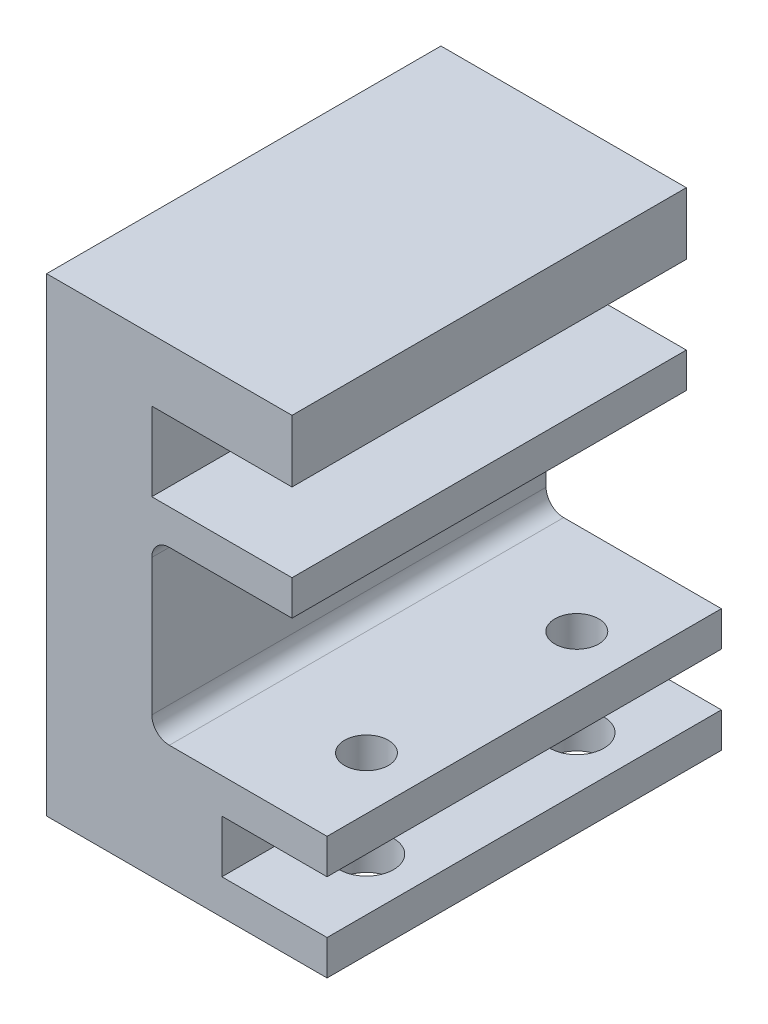
SolidWorks part; units mm, degrees
ref_plane "Front Plane" through (0, 0, 0) normal (0, 0, 1) x (1, 0, 0)
ref_plane "Top Plane" through (0, 0, 0) normal (0, 1, 0) x (1, 0, 0)
ref_plane "Right Plane" through (0, 0, 0) normal (1, 0, 0) x (0, 0, -1)
sketch "Sketch1" plane through (0, 0, 0) normal (0, 0, 1) x (1, 0, 0)
  line L1 (-25.4, -42.545) -> (25.4, -42.545)
  line L2 (-25.4, -42.545) -> (-25.4, 42.545)
  line L3 (-25.4, 42.545) -> (25.4, 42.545)
  line L4 (25.4, -42.545) -> (25.4, 42.545)
  line L5 (-25.4, -42.545) -> (25.4, 42.545) construction
  line L6 (-25.4, 42.545) -> (25.4, -42.545) construction
  point P0 (0, 0)
  dimension "D1" = 85.09
  dimension "D2" = 50.8
extrude "Boss-Extrude1" add sketch "Sketch1" along normal mid plane 71.4248
sketch "Sketch2" plane through (0, 0, 35.7124) normal (0, 0, 1) x (1, 0, 0)
  line L0 (-25.4, -42.545) -> (25.4, -42.545) construction
  line L1 (-6.35, 10.7252) -> (25.4, 10.7252)
  line L2 (-6.35, 10.7252) -> (-6.35, -20.32)
  line L3 (-6.35, -20.32) -> (25.4, -20.32)
  line L4 (25.4, 10.7252) -> (25.4, -20.32)
  line L5 (-6.35, 10.7252) -> (25.4, -20.32) construction
  line L6 (-6.35, -20.32) -> (25.4, 10.7252) construction
  line L7 (25.4, -42.545) -> (25.4, 42.545) construction
  point P0 (9.525, -4.7974)
  point P9 (-3.745, 20.5671)
  dimension "D1" = 22.225
  dimension "D2" = 31.0451
  dimension "D3" = 31.75
extrude "Cut-Extrude1" cut sketch "Sketch2" against normal up to next
ref_plane "Plane1" through (3.9688, 28.8925, -16.6687) normal (1, 0, 0) x (0, 0, -1)
sketch "Sketch4" plane through (0, 0, 35.7124) normal (0, 0, 1) x (1, 0, 0)
  line L0 (25.4, 10.7252) -> (25.4, 42.545) construction
  line L1 (-6.35, 17.0752) -> (25.4, 17.0752)
  line L2 (-6.35, 17.0752) -> (-6.35, 31.2992)
  line L3 (-6.35, 31.2992) -> (25.4, 31.2992)
  line L4 (25.4, 17.0752) -> (25.4, 31.2992)
  line L5 (-6.35, 17.0752) -> (25.4, 31.2992) construction
  line L6 (-6.35, 31.2992) -> (25.4, 17.0752) construction
  line L7 (-6.35, 10.7252) -> (-6.35, -20.32) construction
  line L8 (25.4, 10.7252) -> (-6.35, 10.7252) construction
  point P0 (9.525, 24.1872)
  dimension "D1" = 6.35
  dimension "D2" = 14.224
extrude "Cut-Extrude2" cut sketch "Sketch4" against normal through all
sketch "Sketch5" plane through (0, 0, 35.7124) normal (0, 0, 1) x (1, 0, 0)
  line L1 (6.35, -36.195) -> (25.4, -36.195)
  line L2 (6.35, -36.195) -> (6.35, -26.67)
  line L3 (6.35, -26.67) -> (25.4, -26.67)
  line L4 (25.4, -36.195) -> (25.4, -26.67)
  line L5 (6.35, -36.195) -> (25.4, -26.67) construction
  line L6 (6.35, -26.67) -> (25.4, -36.195) construction
  point P0 (15.875, -31.4325)
  point P5 (0, 0)
  point P7 (0, 0)
extrude "Cut-Extrude3" cut sketch "Sketch5" against normal up to next
sketch "Sketch6" plane through (0, 0, 35.7124) normal (0, 0, 1) x (1, 0, 0)
  line L0 (25.4, 10.7252) -> (-6.35, 10.7252) construction
  line L1 (19.05, 42.545) -> (25.4, 42.545)
  line L2 (19.05, 42.545) -> (19.05, 10.7252)
  line L3 (19.05, 10.7252) -> (25.4, 10.7252)
  line L4 (25.4, 42.545) -> (25.4, 10.7252)
  line L5 (19.05, 42.545) -> (25.4, 10.7252) construction
  line L6 (19.05, 10.7252) -> (25.4, 42.545) construction
  point P0 (22.225, 26.6351)
  point P5 (26.6487, -0.3804)
  point P6 (0, 0)
  point P8 (20.1934, 4.9427)
  dimension "D1" = 6.35
extrude "Cut-Extrude4" cut sketch "Sketch6" against normal up to next and the other way through all
sketch "Sketch7" plane through (-25.4, 0, 0) normal (-1, 0, 0) x (0, 0, 1)
  circle A0 centre (0, 24.13) radius 1.65 construction
  point P0 (0, 24.13)
hole_wizard "#10 Clearance Hole1" positions "Sketch8" profile "Sketch9" hole size "#10" standard "ANSI Inch" end condition up to next
sketch "Sketch8" plane through (-25.4, 0, 0) normal (-1, 0, 0) x (0, 0, 1)
  point P0 (0, 24.13)
sketch "Sketch9" plane through (-25.4, 24.13, 0) normal (0, 1, 0) x (0, 0, 1)
  line L0 (0, 0) -> (0, 19.05)
  line L1 (0, 19.05) -> (2.4892, 19.05)
  line L2 (2.4892, 19.05) -> (2.4892, 0)
  line L5 (2.4892, 0) -> (0, 0)
  line L11 (0, -6.35) -> (0, 107.95) construction
  dimension "Thru Hole Dia." = 4.9784
  dimension "Thru Hole Depth" = 19.05
sketch "Sketch10" plane through (0, -42.545, 0) normal (0, -1, 0) x (1, 0, 0)
  point P0 (15.875, 19.05)
  point P1 (15.875, -19.05)
hole_wizard "3/8 Clearance Hole1" positions "Sketch11" profile "Sketch12" hole size "3/8" standard "ANSI Inch"
sketch "Sketch11" plane through (0, -42.545, 0) normal (0, -1, 0) x (-1, 0, 0)
  point P0 (-15.875, -19.05)
  point P3 (-15.875, 19.05)
sketch "Sketch12" plane through (15.875, -42.545, 19.05) normal (1, 0, 0) x (0, 0, -1)
  line L0 (0, 0) -> (0, 6.35)
  line L1 (0, 6.35) -> (4.9022, 6.35)
  line L2 (4.9022, 6.35) -> (4.9022, 0)
  line L5 (4.9022, 0) -> (0, 0)
  line L11 (0, -6.35) -> (0, 107.95) construction
  dimension "Thru Hole Dia." = 9.8044
  dimension "Thru Hole Depth" = 6.35
hole_wizard "3/8-16 Tapped Hole1" positions "Sketch13" profile "Sketch15" tap size "3/8-16" standard "ANSI Inch"
sketch "Sketch13" plane through (0, -20.32, 0) normal (0, 1, 0) x (1, 0, 0)
  point P0 (15.875, -19.05)
  point P3 (15.875, 19.05)
sketch "Sketch15" plane through (15.875, -20.32, 19.05) normal (1, 0, 0) x (0, 0, 1)
  line L0 (0, 0) -> (0, 6.35)
  line L1 (0, 6.35) -> (3.9687, 6.35)
  line L2 (3.9687, 6.35) -> (3.9687, 0)
  line L5 (3.9687, 0) -> (0, 0)
  line L11 (0, -6.35) -> (0, 107.95) construction
  dimension "Thru Tap Drill Dia." = 7.9375
  dimension "Thru Tap Drill Depth" = 6.35
cosmetic thread "Hole Thread1" parameters "D2"=9.525
cosmetic thread "Hole Thread2" parameters "D2"=9.525
fillet "Fillet1" radius 3.175 2 edges at (-6.35, 10.7252, 0) (-6.35, -20.32, 0)
